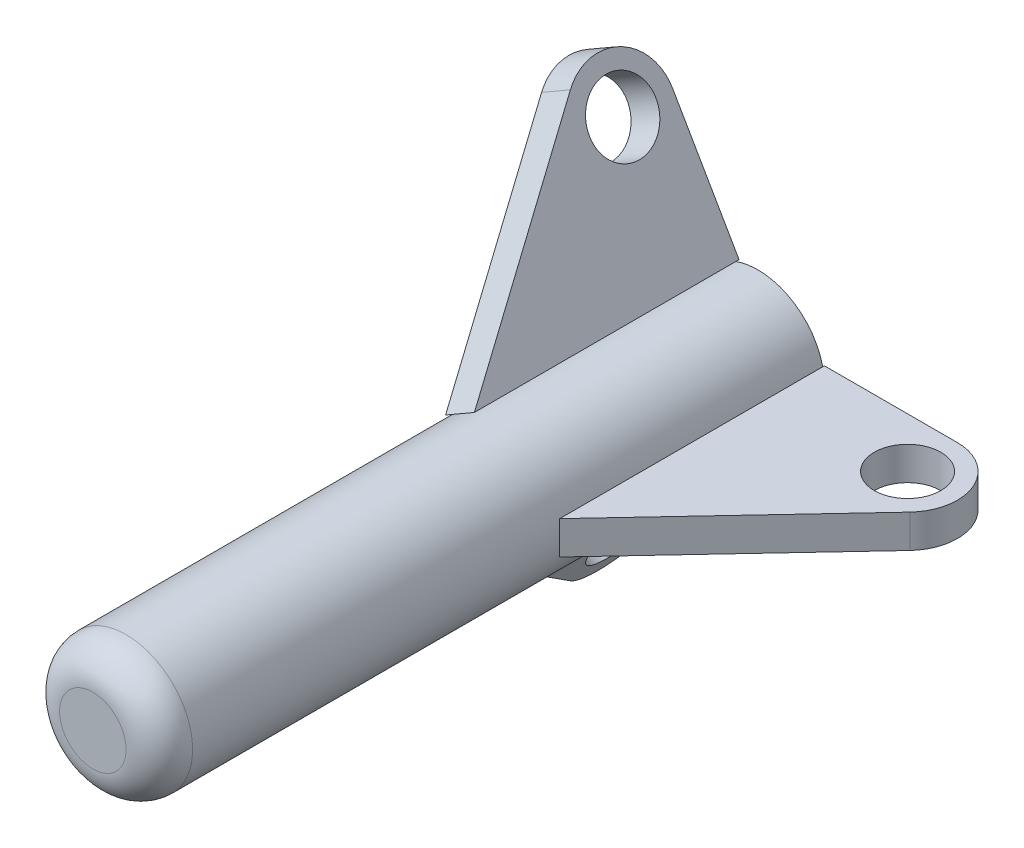
SolidWorks part; units mm, degrees
ref_plane "Front Plane" through (0, 0, 0) normal (0, 0, 1) x (1, 0, 0)
ref_plane "Top Plane" through (0, 0, 0) normal (0, 1, 0) x (1, 0, 0)
ref_plane "Right Plane" through (0, 0, 0) normal (1, 0, 0) x (0, 0, -1)
sketch "Sketch2" plane through (0, 0, 0) normal (0, 0, 1) x (1, 0, 0)
  circle A0 centre (0, 0) radius 20
  dimension "D1" = 40
extrude "Boss-Extrude1" add sketch "Sketch2" along normal blind 200
fillet "Fillet1" radius 10 1 edges at (20, 0, 200)
sketch "Sketch4" plane through (0, 0, 0) normal (0, 1, 0) x (1, 0, 0)
  line L0 (20, 0) -> (-20, 0) construction
  line L1 (20, 0) -> (-20, 0)
  line L2 (20, 0) -> (60, 0)
  line L4 (20, -190) -> (20, 0) construction
  line L5 (20, 0) -> (20, -79.6)
  line L6 (70.9432, -25.259) -> (20, -79.6)
  arc A0 (60, 0) -> (70.9432, -25.259) centre (60, -15) cw
  circle A1 centre (60, -15) radius 10
  dimension "D4" = 20
  dimension "D1" = 60
  dimension "D2" = 79.6
  dimension "D3" = 15
extrude "Boss-Extrude3" add sketch "Sketch4" along normal mid plane 10 separate body contours A0 L2 L5 L6 A1
pattern_circular "CirPattern4" count 3 over 360 about axis through (0, 0, 0) along (0, 0, 1) of bodies 104
